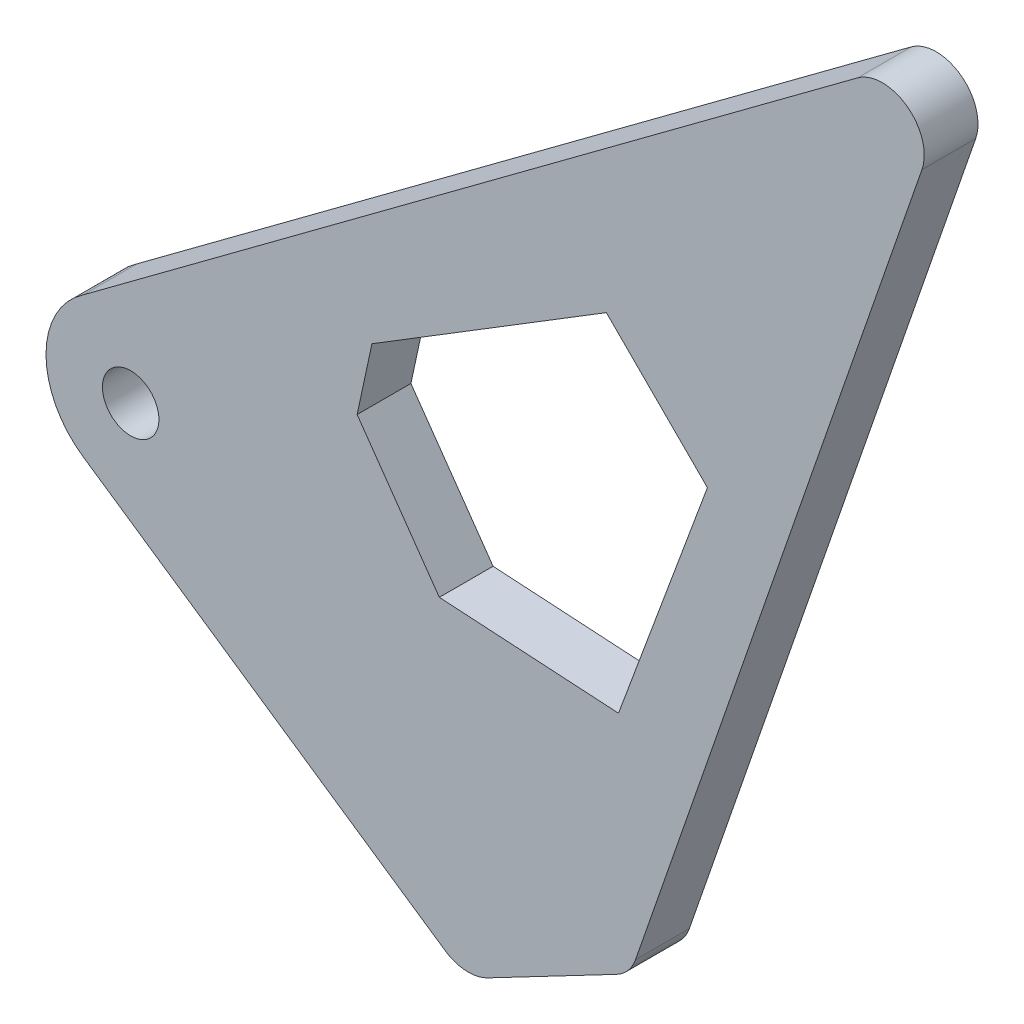
SolidWorks part; units mm, degrees
ref_plane "Front Plane" through (0, 0, 0) normal (0, 0, 1) x (1, 0, 0)
ref_plane "Top Plane" through (0, 0, 0) normal (0, 1, 0) x (1, 0, 0)
ref_plane "Right Plane" through (0, 0, 0) normal (1, 0, 0) x (0, 0, -1)
sketch "Sketch1" plane through (0, 0, 0) normal (0, 0, 1) x (1, 0, 0)
  line L0 (-80.3108, -41.2863) -> (-144.4368, 2.4113)
  line L1 (-144.4368, 27.2026) -> (-7.2583, 129.0829)
  line L2 (-72.7689, -41.7232) -> (-49.9662, -29.7809)
  line L3 (-46.5758, -25.8427) -> (4.1545, 120.7158)
  circle A0 centre (-135.99, 14.807) radius 15
  circle A1 centre (-76.1757, -35.2182) radius 7.3431
  circle A2 centre (-53.2361, -23.5373) radius 7.0481
  circle A3 centre (-2.8432, 123.138) radius 7.405
extrude "Boss-Extrude1" add sketch "Sketch1" along normal mid plane 9.525 contours A0 | A3 L1 A0 L0 A1 L2 A2 L3 | A1 | A2 | A3 A2
sketch "Sketch2" plane through (0, 0, -4.7625) normal (0, 0, -1) x (-1, 0, 0)
  circle A0 centre (59.1354, 44.1102) radius 14.351
sketch "Sketch3" plane through (0, 0, -4.7625) normal (0, 0, -1) x (-1, 0, 0)
  circle A0 centre (135.99, 14.807) radius 5
  dimension "D1" = 10
extrude "Cut-Extrude1" cut sketch "Sketch3" against normal up to surface (9.525 mm away) up to face at (-68.0937, 17.9528, 4.7625)
sketch "Sketch5" plane through (0, 0, -4.7625) normal (0, 0, -1) x (-1, 0, 0)
  line L0 (51.7381, 70.8358) -> (33.8415, 52.9392)
  line L1 (33.8415, 52.9392) -> (49.5906, 10.4646)
  line L2 (49.5906, 10.4646) -> (81.3272, 12.3736)
  line L3 (81.3272, 12.3736) -> (95.8831, 33.1336)
  line L4 (95.8831, 33.1336) -> (93.2583, 45.3033)
  line L5 (93.2583, 45.3033) -> (51.7381, 70.8358)
  point P2 (93.2583, 45.3033)
extrude "Cut-Extrude2" cut sketch "Sketch5" against normal blind 18.375
